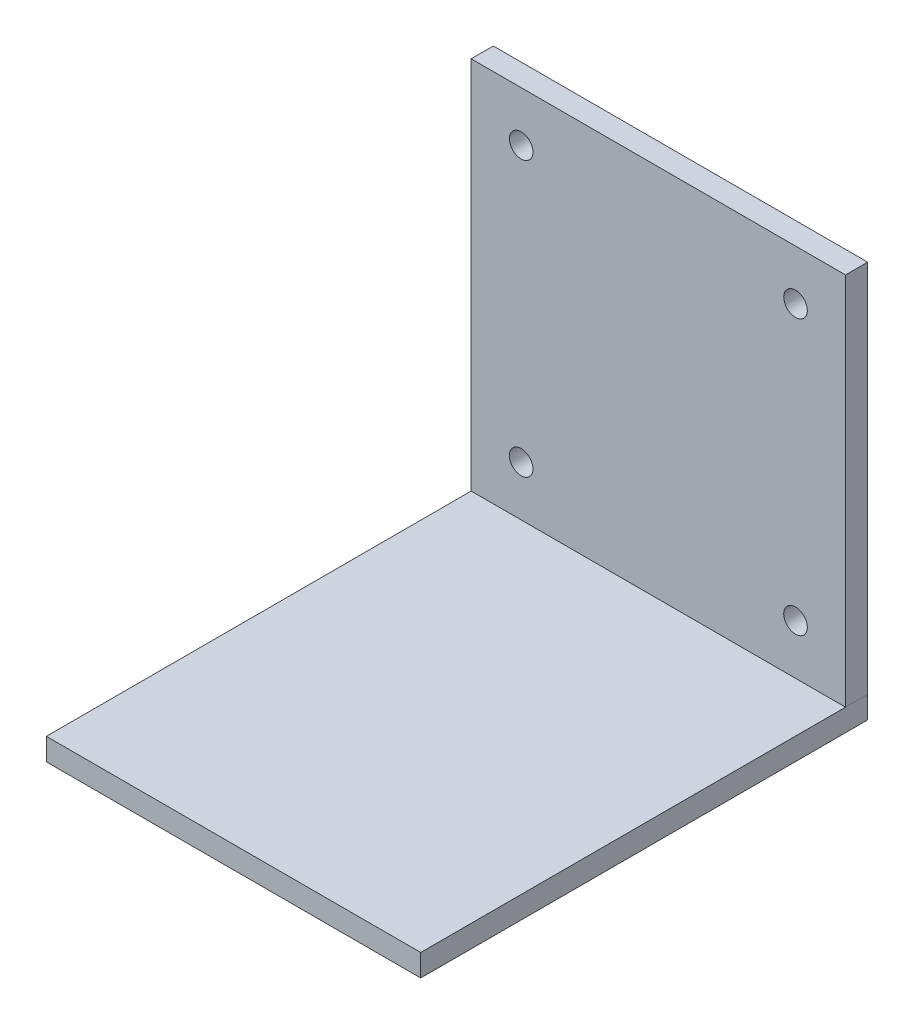
SolidWorks part; units mm, degrees
ref_plane "Front Plane" through (0, 0, 0) normal (0, 0, 1) x (1, 0, 0)
ref_plane "Top Plane" through (0, 0, 0) normal (0, 1, 0) x (1, 0, 0)
ref_plane "Right Plane" through (0, 0, 0) normal (1, 0, 0) x (0, 0, -1)
sketch "Sketch1" plane through (0, 0, 0) normal (0, 0, 1) x (1, 0, 0)
  line L0 (-21.15, 0) -> (21.15, 0)
  line L1 (-21.15, -21.15) -> (21.15, -21.15)
  line L2 (-21.15, -21.15) -> (-21.15, 21.15)
  line L3 (-21.15, 21.15) -> (21.15, 21.15)
  line L4 (21.15, -21.15) -> (21.15, 21.15)
  line L5 (-21.15, -21.15) -> (21.15, 21.15) construction
  line L6 (-21.15, 21.15) -> (21.15, -21.15) construction
  line L7 (0, 21.15) -> (0, -21.15)
  line L8 (-15.5, 21.15) -> (15.5, 21.15)
  line L9 (-15.5, -21.15) -> (15.5, -21.15)
  line L10 (21.15, 0) -> (21.15, 15.5) construction
  line L11 (-21.15, -15.5) -> (-21.15, 15.5)
  line L12 (-21.15, 15.5) -> (21.15, 15.5)
  line L13 (-21.15, -15.5) -> (21.15, -15.5)
  line L14 (-15.5, 21.15) -> (-15.5, -21.15)
  line L15 (15.5, 21.15) -> (15.5, -21.15)
  point P0 (0, 0)
  point P13 (0, 21.15)
  point P16 (0, -21.15)
  point P20 (-21.15, 0)
  dimension "D1" = 42.3
  dimension "D2" = 15.5
  dimension "D3" = 15.5
  dimension "D4" = 15.5
  dimension "D5" = 15.5
sketch "Sketch2" plane through (0, 0, 0) normal (0, 0, 1) x (1, 0, 0)
  line L1 (-21.15, -21.15) -> (21.15, -21.15)
  line L2 (-21.15, -21.15) -> (-21.15, 21.15)
  line L3 (-21.15, 21.15) -> (21.15, 21.15)
  line L4 (21.15, -21.15) -> (21.15, 21.15)
  line L5 (-21.15, -21.15) -> (21.15, 21.15) construction
  line L6 (-21.15, 21.15) -> (21.15, -21.15) construction
  line L8 (-21.15, -21.15) -> (21.15, 21.15) construction
  line L9 (-21.15, 21.15) -> (21.15, 21.15) construction
  circle A0 centre (-15.5, 15.5) radius 1.3335
  circle A1 centre (15.5, 15.5) radius 1.3335
  circle A2 centre (15.5, -15.5) radius 1.3335
  circle A3 centre (-15.5, -15.5) radius 1.3335
  point P0 (0, 0)
  dimension "D2" = 2.667
  dimension "D1" = 42.3
ref_point "Point1"
ref_point "Point2"
ref_point "Point3"
ref_point "Point4"
extrude "Boss-Extrude1" add sketch "Sketch2" along normal blind 2.5
sketch "Sketch3" plane through (0, -21.15, 0) normal (0, -1, 0) x (1, 0, 0)
  line L1 (21.15, 2.5) -> (21.15, 50.5)
  line L2 (-21.15, 2.5) -> (-21.15, 50.5)
  line L3 (21.15, 50.5) -> (-21.15, 50.5)
  line L4 (21.15, 0) -> (-21.15, 0)
  line L5 (21.15, 0) -> (21.15, 2.5)
  line L6 (-21.15, 0) -> (-21.15, 2.5)
  dimension "D1" = 48
extrude "Boss-Extrude2" add sketch "Sketch3" along normal blind 2.5 separate body
